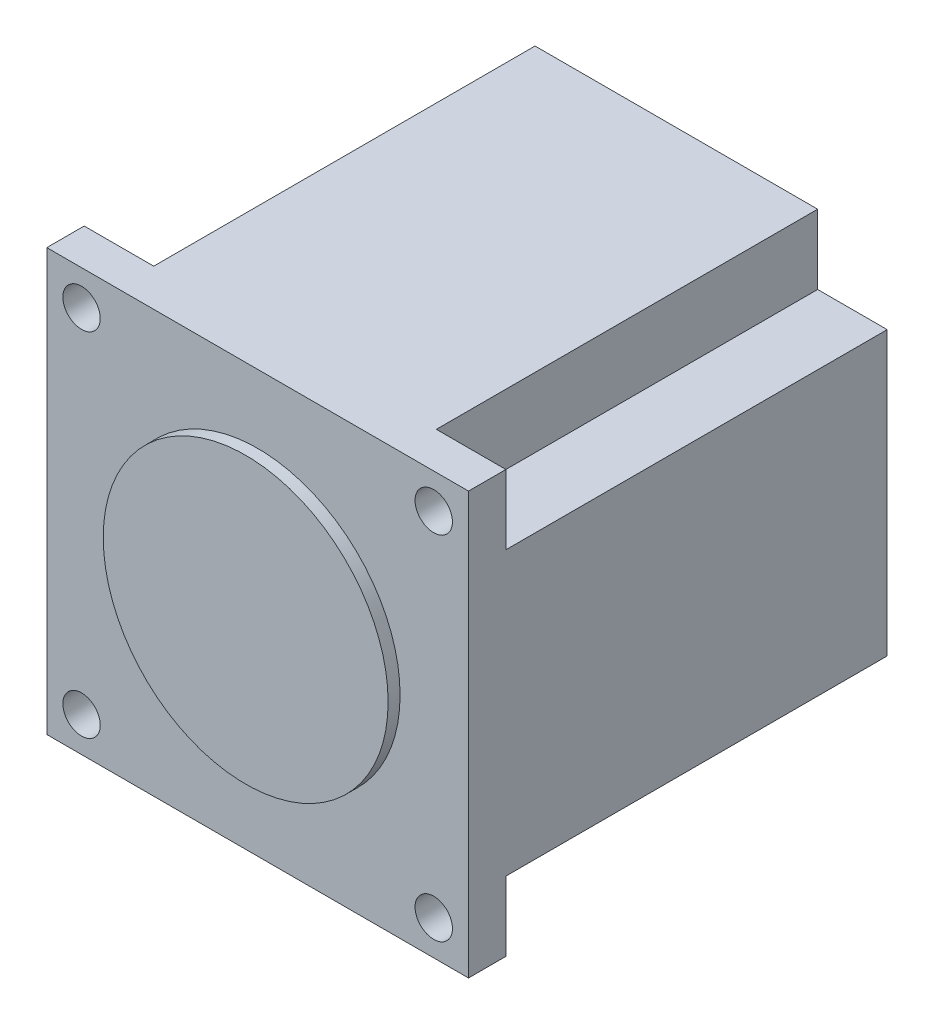
SolidWorks part; units mm, degrees
ref_plane "Front Plane" through (0, 0, 0) normal (0, 0, 1) x (1, 0, 0)
ref_plane "Top Plane" through (0, 0, 0) normal (0, 1, 0) x (1, 0, 0)
ref_plane "Right Plane" through (0, 0, 0) normal (1, 0, 0) x (0, 0, -1)
sketch "Sketch2" plane through (0, 0, 0) normal (0, 0, 1) x (1, 0, 0)
  line L0 (-18.9, 28.2) -> (18.9, 28.2)
  line L1 (18.9, 28.2) -> (18.9, 18.9)
  line L2 (18.9, 18.9) -> (28.2, 18.9)
  line L3 (28.2, 18.9) -> (28.2, -18.9)
  line L4 (28.2, -18.9) -> (18.9, -18.9)
  line L5 (18.9, -18.9) -> (18.9, -28.2)
  line L6 (18.9, -28.2) -> (-18.9, -28.2)
  line L7 (-18.9, -28.2) -> (-18.9, -18.9)
  line L8 (-18.9, -18.9) -> (-28.2, -18.9)
  line L9 (-28.2, -18.9) -> (-28.2, 18.9)
  line L10 (-28.2, 18.9) -> (-18.9, 18.9)
  line L11 (-18.9, 18.9) -> (-18.9, 28.2)
  point P12 (-28.2, 0)
  point P14 (28.2, 0)
  point P15 (0, -28.2)
  point P16 (0, 28.2)
  point P17 (-23.55, -18.9)
  point P18 (23.55, -18.9)
  dimension "D1" = 56.4
  dimension "D2" = 56.4
  dimension "D3" = 47.1
extrude "Boss-Extrude2" add sketch "Sketch2" along normal blind 51
sketch "Sketch3" plane through (0, 0, 51) normal (0, 0, 1) x (1, 0, 0)
  line L0 (18.9, 28.2) -> (-18.9, 28.2) construction
  line L1 (-28.2, -28.2) -> (28.2, -28.2)
  line L2 (-28.2, -28.2) -> (-28.2, 28.2)
  line L3 (-28.2, 28.2) -> (28.2, 28.2)
  line L4 (28.2, -28.2) -> (28.2, 28.2)
  line L5 (-28.2, -28.2) -> (28.2, 28.2) construction
  line L6 (-28.2, 28.2) -> (28.2, -28.2) construction
  line L7 (-28.2, 18.9) -> (-28.2, -18.9) construction
  line L8 (28.2, 18.9) -> (18.9, 18.9) construction
  line L9 (-18.9, 18.9) -> (-28.2, 18.9) construction
  line L10 (-28.2, -18.9) -> (-18.9, -18.9) construction
  line L11 (18.9, -18.9) -> (28.2, -18.9) construction
  circle A0 centre (-23.55, 23.55) radius 2.5
  circle A1 centre (23.55, 23.55) radius 2.5
  circle A2 centre (23.55, -23.55) radius 2.5
  circle A3 centre (-23.55, -23.55) radius 2.5
  point P1 (0, 0)
  point P21 (23.55, 18.9)
  point P25 (-23.55, 18.9)
  point P29 (-23.55, -18.9)
  point P33 (23.55, -18.9)
  dimension "D1" = 5
  dimension "D2" = 5
  dimension "D3" = 5
  dimension "D4" = 5
extrude "Boss-Extrude3" add sketch "Sketch3" along normal blind 5
sketch "Sketch4" plane through (0, 0, 56) normal (0, 0, 1) x (1, 0, 0)
  circle A0 centre (0, 0) radius 19.05
  dimension "D1" = 38.1
extrude "Boss-Extrude4" add sketch "Sketch4" along normal blind 1.6
